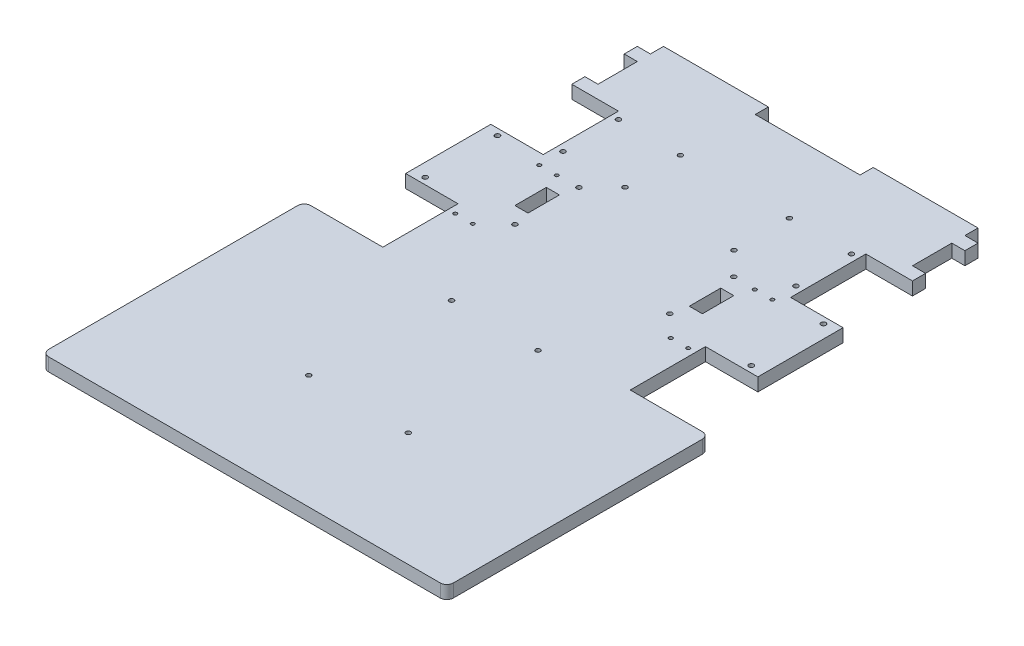
SolidWorks part; units mm, degrees
ref_plane "Front Plane" through (0, 0, 0) normal (0, 0, 1) x (1, 0, 0)
ref_plane "Top Plane" through (0, 0, 0) normal (0, 1, 0) x (1, 0, 0)
ref_plane "Right Plane" through (0, 0, 0) normal (1, 0, 0) x (0, 0, -1)
sketch "Sketch1" plane through (0, 0, 0) normal (0, 1, 0) x (1, 0, 0)
  line L0 (-147.6422, 18.3147) -> (-147.6422, -22.9603)
  line L1 (-138.4922, 92.8637) -> (-87.6922, 92.8637)
  line L2 (-122.2422, 54.7637) -> (-144.8422, 54.7637)
  line L3 (-62.2922, 86.5137) -> (-62.2922, -186.4093)
  line L4 (-62.2922, -186.4093) -> (-157.1672, -186.4093)
  line L5 (-144.8422, 54.7637) -> (-144.8422, 61.1137)
  line L6 (-144.8422, 80.1637) -> (-144.8422, 86.5137)
  line L7 (-147.6422, 18.3147) -> (-122.2422, 18.3147)
  line L8 (-122.2422, 54.7637) -> (-122.2422, 18.3147)
  line L9 (-147.6422, -22.9603) -> (-122.2422, -22.9603)
  line L10 (-107.7247, -9.9428) -> (-101.3747, -9.9428)
  line L11 (-160.3422, -183.2343) -> (-160.3422, -62.5843)
  line L12 (-122.2422, -22.9603) -> (-122.2422, -59.4093)
  line L13 (-157.1672, -59.4093) -> (-122.2422, -59.4093)
  line L14 (-107.7247, -9.9428) -> (-107.7247, 5.2972)
  line L15 (-107.7247, 5.2972) -> (-101.3747, 5.2972)
  line L16 (-101.3747, -9.9428) -> (-101.3747, 5.2972)
  line L17 (-107.7247, -9.9428) -> (-101.3747, 5.2972) construction
  line L18 (-107.7247, 5.2972) -> (-101.3747, -9.9428) construction
  line L21 (-144.8422, 86.5137) -> (-138.4922, 86.5137)
  line L22 (-138.4922, 92.8637) -> (-138.4922, 86.5137)
  line L23 (-144.8422, 80.1637) -> (-138.4922, 80.1637)
  line L25 (-144.8422, 61.1137) -> (-138.4922, 61.1137)
  line L26 (-138.4922, 80.1637) -> (-138.4922, 61.1137)
  line L27 (-62.2922, 86.5137) -> (-87.6922, 86.5137)
  line L28 (-87.6922, 92.8637) -> (-87.6922, 86.5137)
  circle A0 centre (-118.7497, -27.8153) radius 0.889
  circle A1 centre (-118.7497, 12.9197) radius 0.889
  circle A2 centre (-110.2647, 12.9197) radius 0.889
  circle A3 centre (-110.2647, -27.8153) radius 0.889
  circle A4 centre (-118.7497, 51.2712) radius 1.1303
  circle A5 centre (-118.7497, 24.398) radius 1.1303
  circle A6 centre (-88.7015, 51.2712) radius 1.1303
  circle A7 centre (-88.7015, 24.398) radius 1.1303
  circle A8 centre (-99.7922, 13.1772) radius 1.1303
  circle A9 centre (-99.7922, -17.8228) radius 1.1303
  circle A10 centre (-83.2472, -65.1243) radius 1.1303
  circle A11 centre (-86.4222, -131.1643) radius 1.1303
  arc A12 (-157.1672, -186.4093) -> (-160.3422, -183.2343) centre (-157.1672, -183.2343) cw
  arc A13 (-160.3422, -62.5843) -> (-157.1672, -59.4093) centre (-157.1672, -62.5843) cw
  point P14 (-104.5497, -2.3228)
  point P49 (-160.3422, -186.4093)
  point P52 (-160.3422, -59.4093)
  dimension "D9" = 1.778
  dimension "D10" = 1.778
  dimension "D11" = 3.4925
  dimension "D12" = 3.4925
  dimension "D14" = 4.855
  dimension "D21" = 3.4925
  dimension "D22" = 3.4925
  dimension "D23" = 26.8732
  dimension "D24" = 30.0482
  dimension "D25" = 2.2606
  dimension "D26" = 2.2606
  dimension "D27" = 2.2606
  dimension "D28" = 2.2606
  dimension "D35" = 2.2606
  dimension "D36" = 2.2606
  dimension "D37" = 31
  dimension "D38" = 15.5
  dimension "D39" = 37.5
  dimension "D41" = 2.2606
  dimension "D42" = 20.955
  dimension "D43" = 2.2606
  dimension "D44" = 66.04
  dimension "D45" = 24.13
  dimension "D46" = 3.175
  dimension "D1" = 41.275
  dimension "D2" = 25.4
  dimension "D3" = 25.4
  dimension "D4" = 36.449
  dimension "D5" = 36.449
  dimension "D6" = 22.6
  dimension "D7" = 38.1
  dimension "D13" = 5.395
  dimension "D16" = 2.54
  dimension "D17" = 15.24
  dimension "D18" = 20.6375
  dimension "D19" = 6.35
  dimension "D20" = 127
  dimension "D29" = 6.35
  dimension "D30" = 6.35
  dimension "D31" = 6.35
  dimension "D32" = 6.35
  dimension "D33" = 6.35
  dimension "D34" = 0
  dimension "D40" = 5.715
  dimension "D47" = 6.35
  dimension "D48" = 25.4
  dimension "D15" = 2
extrude "Boss-Extrude1" add sketch "Sketch1" along normal blind 6.35
sketch "Sketch2" plane through (0, 6.35, 0) normal (0, 1, 0) x (1, 0, 0)
  line L0 (-147.6422, 18.3147) -> (-147.6422, -22.9603) construction
  circle A0 centre (-141.2922, 15.1772) radius 1.1684
  circle A1 centre (-141.2922, -19.8228) radius 1.1684
  point P6 (-147.6422, -2.3228)
  point P7 (-147.6422, -2.3228)
  dimension "D1" = 2.3368
  dimension "D2" = 2.3368
  dimension "D3" = 6.35
  dimension "D4" = 6.35
  dimension "D5" = 17.5
  dimension "D6" = 17.5
extrude "Cut-Extrude1" cut sketch "Sketch2" against normal blind 6.35
mirror "Mirror1" about plane through (-62.2922, 6.35, -86.5137) normal (-1, 0, 0) of "Cut-Extrude1", "Boss-Extrude1"
